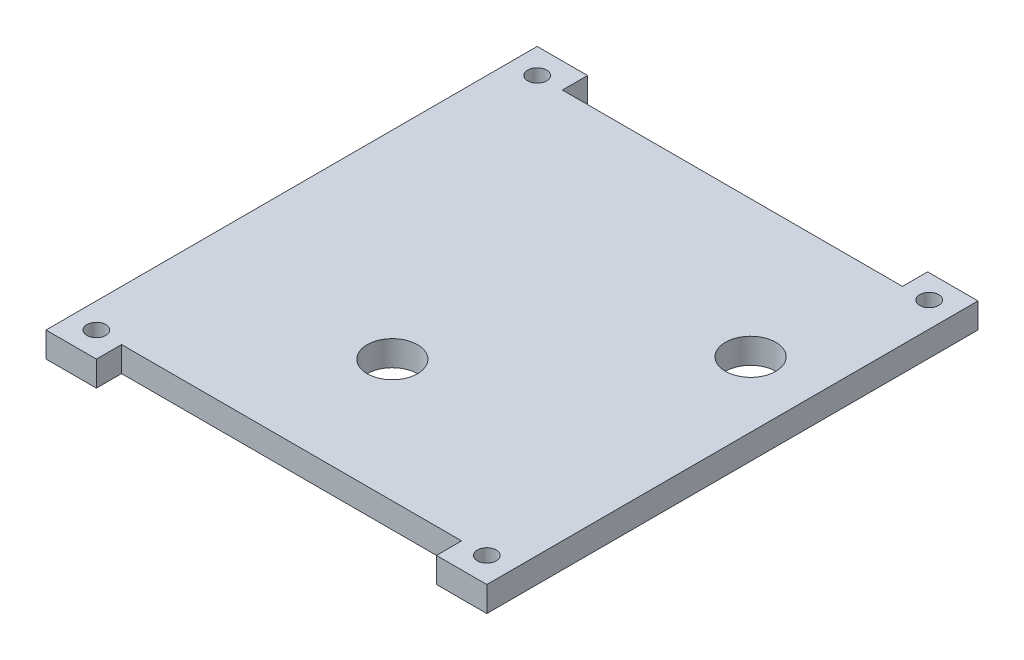
SolidWorks part; units mm, degrees
ref_plane "Front Plane" through (0, 0, 0) normal (0, 0, 1) x (1, 0, 0)
ref_plane "Top Plane" through (0, 0, 0) normal (0, 1, 0) x (1, 0, 0)
ref_plane "Right Plane" through (0, 0, 0) normal (1, 0, 0) x (0, 0, -1)
sketch "Sketch1" plane through (0, 4.3906, 0) normal (0, 1, 0) x (1, 0, 0)
  line L24 (10.961, 31.7266) -> (10.961, -7.2734)
  line L25 (10.961, -7.2734) -> (14.961, -7.2734)
  line L26 (14.961, -7.2734) -> (14.961, -5.2734)
  line L27 (14.961, -5.2734) -> (41.961, -5.2734)
  line L28 (41.961, -5.2734) -> (41.961, -7.2734)
  line L29 (41.961, -7.2734) -> (45.961, -7.2734)
  line L30 (45.961, -7.2734) -> (45.961, 31.7266)
  line L31 (45.961, 31.7266) -> (41.961, 31.7266)
  line L32 (41.961, 31.7266) -> (41.961, 29.7266)
  line L33 (41.961, 29.7266) -> (14.961, 29.7266)
  line L34 (14.961, 29.7266) -> (14.961, 31.7266)
  line L35 (14.961, 31.7266) -> (10.961, 31.7266)
  line L36 (10.961, 31.7266) -> (10.961, -7.2734)
  line L37 (10.961, -7.2734) -> (14.961, -7.2734)
  line L38 (14.961, -7.2734) -> (14.961, -5.2734)
  line L39 (14.961, -5.2734) -> (41.961, -5.2734)
  line L40 (41.961, -5.2734) -> (41.961, -7.2734)
  line L41 (41.961, -7.2734) -> (45.961, -7.2734)
  line L42 (45.961, -7.2734) -> (45.961, 31.7266)
  line L43 (45.961, 31.7266) -> (41.961, 31.7266)
  line L44 (41.961, 31.7266) -> (41.961, 29.7266)
  line L45 (41.961, 29.7266) -> (14.961, 29.7266)
  line L46 (14.961, 29.7266) -> (14.961, 31.7266)
  line L47 (14.961, 31.7266) -> (10.961, 31.7266)
  circle A0 centre (12.961, -5.2734) radius 0.75 construction
  circle A1 centre (43.961, -5.2734) radius 0.75 construction
  circle A2 centre (43.961, 29.8492) radius 0.75 construction
  circle A3 centre (12.961, 29.7266) radius 0.75 construction
  circle A4 centre (12.961, -5.2734) radius 0.75
  circle A5 centre (43.961, -5.2734) radius 0.75
  circle A6 centre (43.961, 29.8492) radius 0.75
  circle A7 centre (12.961, 29.7266) radius 0.75
  dimension "D1" = 0
extrude "Boss-Extrude1" add sketch "Sketch1" along normal blind 2
sketch "Sketch2" plane through (0, 6.3906, 0) normal (0, 1, 0) x (1, 0, 0)
  circle A0 centre (26.7182, 4.468) radius 2
  circle A1 centre (40.7765, 18.8579) radius 2
  point P2 (40.7765, 18.8579)
  dimension "D1" = 4
  dimension "D2" = 4
extrude "Cut-Extrude1" cut sketch "Sketch2" against normal blind 2
